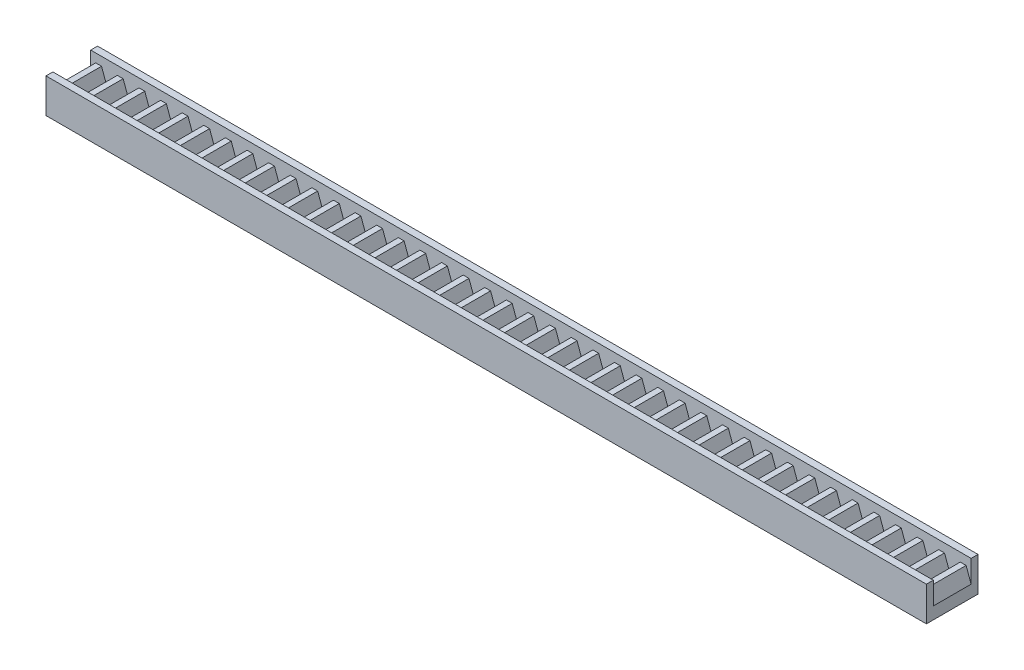
SolidWorks part; units mm, degrees
ref_plane "Front Plane" through (0, 0, 0) normal (0, 0, 1) x (1, 0, 0)
ref_plane "Top Plane" through (0, 0, 0) normal (0, 1, 0) x (1, 0, 0)
ref_plane "Right Plane" through (0, 0, 0) normal (1, 0, 0) x (0, 0, -1)
sketch "Sketch1" plane through (0, 0, 0) normal (0, 0, 1) x (1, 0, 0)
  line L1 (-127, 1.5) -> (127, 1.5)
  line L2 (-127, 1.5) -> (-127, -1.5)
  line L3 (-127, -1.5) -> (127, -1.5)
  line L4 (127, 1.5) -> (127, -1.5)
  line L5 (-127, 1.5) -> (127, -1.5) construction
  line L6 (-127, -1.5) -> (127, 1.5) construction
  point P0 (0, 0)
  dimension "D1" = 254
  dimension "D2" = 3
extrude "Boss-Extrude1" add sketch "Sketch1" along normal mid plane 11
sketch "Sketch4" plane through (0, 0, 5.5) normal (0, 0, 1) x (1, 0, 0)
  line L1 (-116.1196, 1.5) -> (-116.1196, 2)
  line L4 (-127, 1.5) -> (-127, 2)
  line L8 (-127, 2) -> (-125.5441, 6)
  line L9 (-125.5441, 6) -> (-123.8585, 6)
  line L10 (-123.8585, 6) -> (-122.4026, 2)
  line L11 (-127, 1.5) -> (-127, -1.5)
  line L13 (-127, -1.5) -> (-116.1196, -1.5)
  line L16 (-119.2611, 6) -> (-120.717, 2)
  line L17 (-117.5755, 6) -> (-119.2611, 6)
  line L18 (-116.1196, 2) -> (-117.5755, 6)
  line L19 (-121.5598, 1.5) -> (-121.5598, 6) construction
  line L20 (127, 1.5) -> (-127, 1.5) construction
  line L21 (-124.7013, 6) -> (-124.7013, 1.5) construction
  line L22 (-118.4183, 6) -> (-118.4183, 1.5) construction
  line L23 (-126.2721, 4) -> (-123.1306, 4) construction
  line L24 (-116.8476, 4) -> (-119.9891, 4) construction
  line L25 (-127, 2) -> (-122.4026, 2) construction
  line L26 (-123.8585, 6) -> (-119.2611, 6) construction
  line L27 (-121.6885, 1.5) -> (-121.4311, 1.5)
  line L28 (-127, -1.5) -> (127, -1.5) construction
  line L29 (-116.1196, -1.5) -> (-116.1196, 1.5)
  arc A1 (-122.4026, 2) -> (-121.6885, 1.5) centre (-121.6885, 2.2599) ccw
  arc A2 (-120.717, 2) -> (-121.4311, 1.5) centre (-121.4311, 2.2599) cw
  point P32 (-124.361, 5.8292)
  point P33 (-124.2079, 6.0875)
  dimension "D5" = 0.7599
  dimension "D1" = 2
  dimension "D2" = 6.283
  dimension "D4" = 0.5
  dimension "D3" = 20
  dimension "D6" = 2.5
  dimension "D7" = 3.1415
extrude "Boss-Extrude2" add sketch "Sketch4" against normal up to surface (11 mm away) up to face at (0, 0, -5.5)
pattern_linear "LPattern2" count 40 spacing 6.2832 along (1, 0, 0) of "Boss-Extrude2"
sketch "Sketch7" plane through (0, 0, 5.5) normal (0, 0, 1) x (1, 0, 0)
  line L0 (128.9252, -1.5) -> (128.9252, 2) construction
  line L1 (-127, -1.5) -> (128.9252, -1.5)
  line L2 (-127, -1.5) -> (-127, 8.5)
  line L3 (-127, 8.5) -> (128.9252, 8.5)
  line L4 (128.9252, -1.5) -> (128.9252, 8.5)
  dimension "D1" = 10
extrude "Boss-Extrude4" add sketch "Sketch7" along normal blind 2
mirror "Mirror2" about plane through (0, 0, 0) normal (0, 0, 1) of "Boss-Extrude4"
equation "\"module\"= 2"
equation "\"number of teeth\"= 24"
equation "\"pressure angle\"= 20"
equation "\"add\" = \"module\""
equation "\"ded\"= \"module\" * 1.25"
equation "\"pitch\"= 3.1415 * \"module\""
equation "\"base pitch\"= \"pitch\" * cos ( \"pressure angle\" )"
equation "\"D1@Sketch4\"=\"add\""
equation "\"D2@Sketch4\"=\"pitch\""
equation "\"bottom clearance\"= \"ded\" - \"add\""
equation "\"root radius\"= \"bottom clearance\" / ( 1 - sin ( \"pressure angle\" ) )"
equation "\"D4@Sketch4\"=\"bottom clearance\""
equation "\"D5@Sketch4\"=\"root radius\""
equation "\"D3@Sketch4\"=\"pressure angle\""
equation "\"D6@Sketch4\"=\"ded\""
equation "\"D7@Sketch4\"=\"pitch\"/2"
